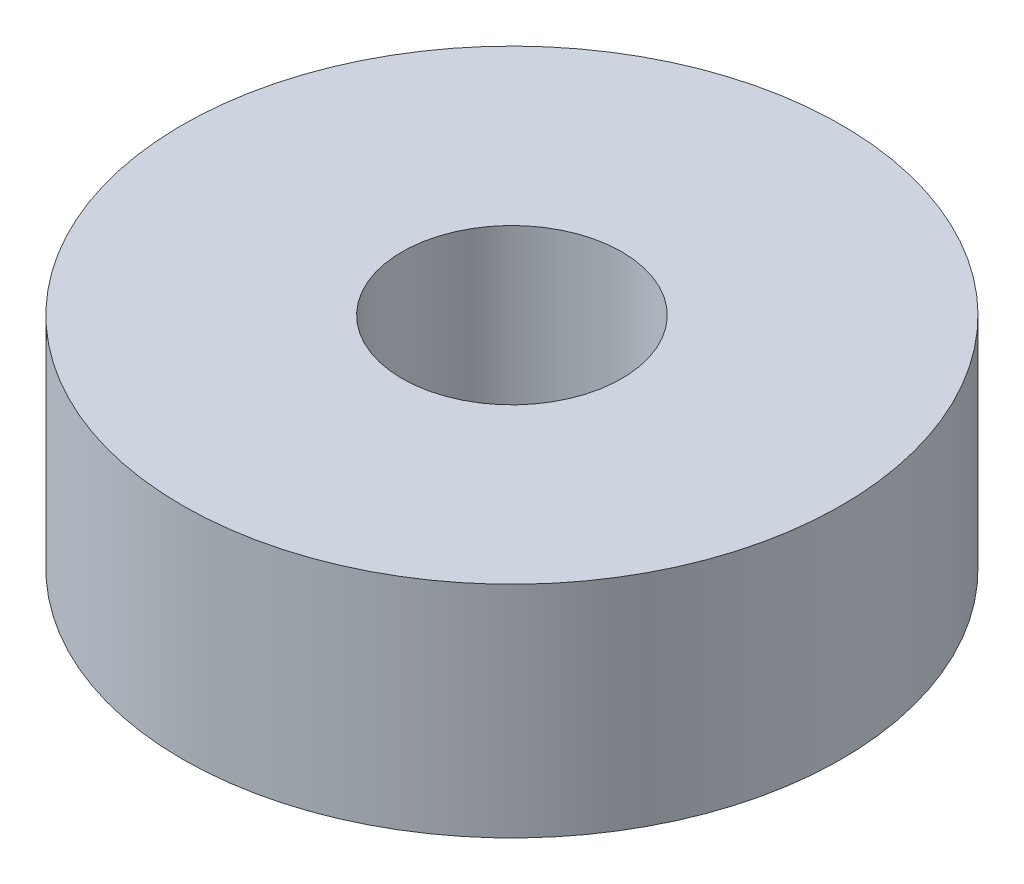
SolidWorks part; units mm, degrees
ref_plane "Front Plane" through (0, 0, 0) normal (0, 0, 1) x (1, 0, 0)
ref_plane "Top Plane" through (0, 0, 0) normal (0, 1, 0) x (1, 0, 0)
ref_plane "Right Plane" through (0, 0, 0) normal (1, 0, 0) x (0, 0, -1)
sketch "Sketch1" plane through (0, 0, 0) normal (0, 1, 0) x (1, 0, 0)
  circle A0 centre (0, 0) radius 3.175
  circle A1 centre (0, 0) radius 9.525
  dimension "D1" = 6.35
  dimension "D2" = 19.05
extrude "Boss-Extrude1" add sketch "Sketch1" along normal blind 6.35
